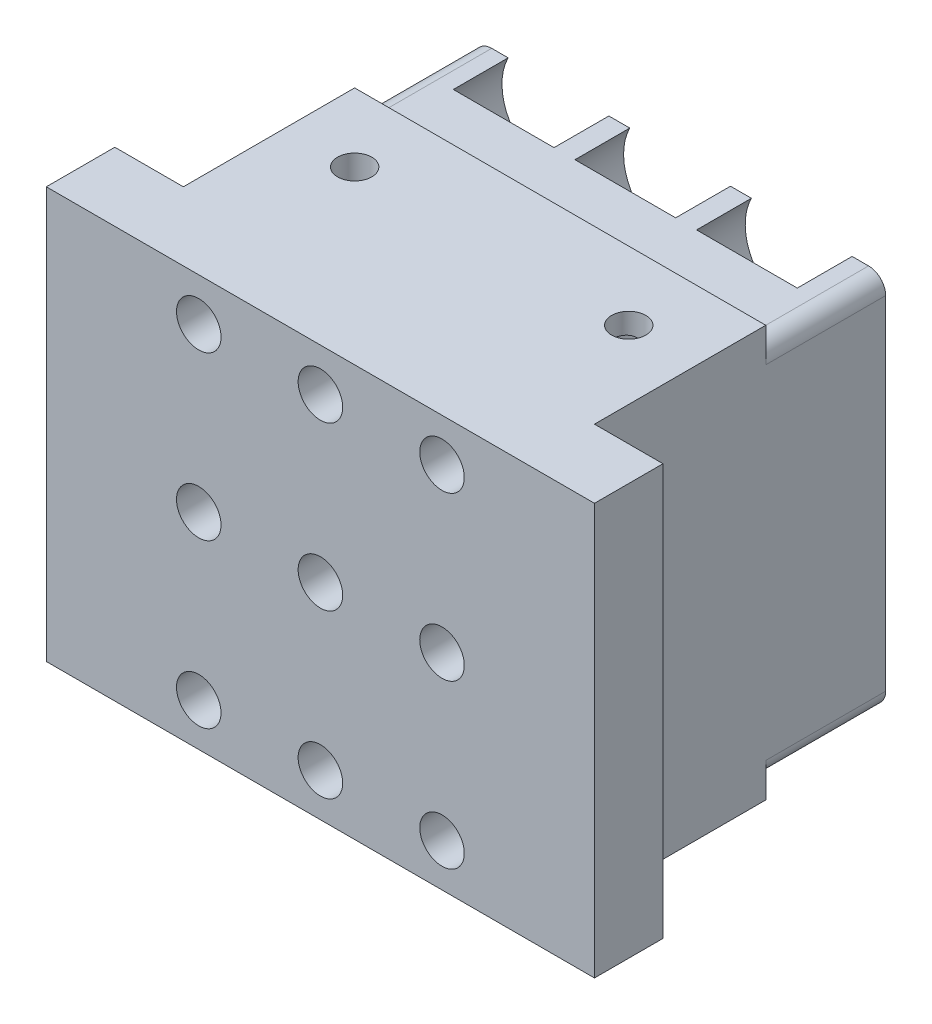
SolidWorks part; units mm, degrees
ref_plane "Front Plane" through (0, 0, 0) normal (0, 0, 1) x (1, 0, 0)
ref_plane "Top Plane" through (0, 0, 0) normal (0, 1, 0) x (1, 0, 0)
ref_plane "Right Plane" through (0, 0, 0) normal (1, 0, 0) x (0, 0, -1)
sketch "Sketch1" plane through (0, 0, 0) normal (0, 1, 0) x (1, 0, 0)
  line L0 (0, 0) -> (8, 0)
  line L1 (8, 0) -> (8, 2)
  line L2 (8, 2) -> (6, 2)
  line L3 (6, 2) -> (6, 7)
  line L8 (6, 7) -> (-6, 7)
  line L9 (-6, 7) -> (-6, 2)
  line L10 (-6, 2) -> (-8, 2)
  line L11 (-8, 2) -> (-8, 0)
  line L12 (-8, 0) -> (0, 0)
  point P15 (0, 7)
  point P16 (0, 7)
  dimension "D1" = 16
  dimension "D2" = 2
  dimension "D5" = 7
  dimension "D6" = 12
extrude "Boss-Extrude1" add sketch "Sketch1" along normal blind 12
sketch "Sketch4" plane through (0, 0, 0) normal (0, 0, 1) x (1, 0, 0)
  line L0 (-5.5, 11) -> (-5.5, 1) construction
  line L2 (-6, 11) -> (-6, 1)
  line L3 (5.5, 11) -> (5.5, 1) construction
  line L4 (6, 11) -> (6, 1)
  line L6 (-5.5, 6) -> (5.5, 6) construction
  line L7 (-8, 12) -> (-8, 0) construction
  line L8 (-5.5, 11.5) -> (5.5, 11.5)
  line L9 (5.5, 0.5) -> (-5.5, 0.5)
  line L10 (-8, 12) -> (8, 0) construction
  arc A0 (-5.5, 11.5) -> (-6, 11) centre (-5.5, 11) ccw
  arc A1 (-6, 1) -> (-5.5, 0.5) centre (-5.5, 1) ccw
  arc A2 (6, 11) -> (5.5, 11.5) centre (5.5, 11) ccw
  arc A3 (5.5, 0.5) -> (6, 1) centre (5.5, 1) ccw
  point P2 (0, 0)
  point P7 (5.5, 6)
  point P12 (0, 0)
  point P13 (6, 6)
  point P16 (0, 6)
  point P19 (-8, 6)
  point P27 (0, 11.5)
  dimension "D1" = 11
  dimension "D2" = 0.5
  dimension "D4" = 12
extrude "Boss-Extrude2" add sketch "Sketch4" against normal blind 10.5
sketch "Sketch2" plane through (0, 12, 0) normal (0, 1, 0) x (1, 0, 0)
  line L0 (-4, 5) -> (-4, 7) construction
  line L2 (-4, 5) -> (4, 5) construction
  line L3 (4, 5) -> (4, 7) construction
  line L5 (-8, 0) -> (8, 0) construction
  circle A0 centre (-4, 5) radius 0.5
  circle A1 centre (4, 5) radius 0.5
  point P6 (0, 5)
  dimension "D1" = 1
  dimension "D2" = 5
  dimension "D3" = 8
extrude "Cut-Extrude1" cut sketch "Sketch2" against normal through all both and the other way through all
sketch "Sketch5" plane through (0, 0, -10.5) normal (0, 0, -1) x (-1, 0, 0)
  line L0 (-3.55, 6) -> (8, 6) construction
  line L4 (8, 12) -> (8, 0) construction
  circle A1 centre (3.55, 6) radius 1.65
  circle A4 centre (-3.55, 6) radius 1.65
  circle A5 centre (0, 6) radius 1.65
  circle A6 centre (-3.55, 10.75) radius 1.65
  circle A7 centre (0, 10.75) radius 1.65
  circle A8 centre (3.55, 10.75) radius 1.65
  circle A9 centre (-3.55, 1.25) radius 1.65
  circle A10 centre (0, 1.25) radius 1.65
  circle A11 centre (3.55, 1.25) radius 1.65
  dimension "D1" = 3.3
  dimension "D2" = 7.1
  dimension "D3" = 3.55
  dimension "D4" = 2
  dimension "D5" = 4.75
  dimension "D7" = 4.75
  dimension "D6" = 2
extrude "Cut-Extrude2" cut sketch "Sketch5" against normal blind 1.6
sketch "Sketch7" plane through (0, 0, -8.9) normal (0, 0, -1) x (-1, 0, 0)
  circle A1 centre (-3.55, 6) radius 0.65
  circle A2 centre (3.55, 6) radius 0.65
  circle A4 centre (0, 6) radius 0.65
  circle A5 centre (-3.55, 6) radius 1.65 construction
  circle A6 centre (0, 6) radius 1.65 construction
  circle A7 centre (-3.55, 1.25) radius 0.65
  circle A8 centre (0, 1.25) radius 0.65
  circle A9 centre (3.55, 1.25) radius 0.65
  circle A10 centre (3.55, 10.75) radius 0.65
  circle A11 centre (0, 10.75) radius 0.65
  circle A12 centre (-3.55, 10.75) radius 0.65
  dimension "D1" = 1.3
extrude "Cut-Extrude5" cut sketch "Sketch7" against normal through all both and the other way through all
